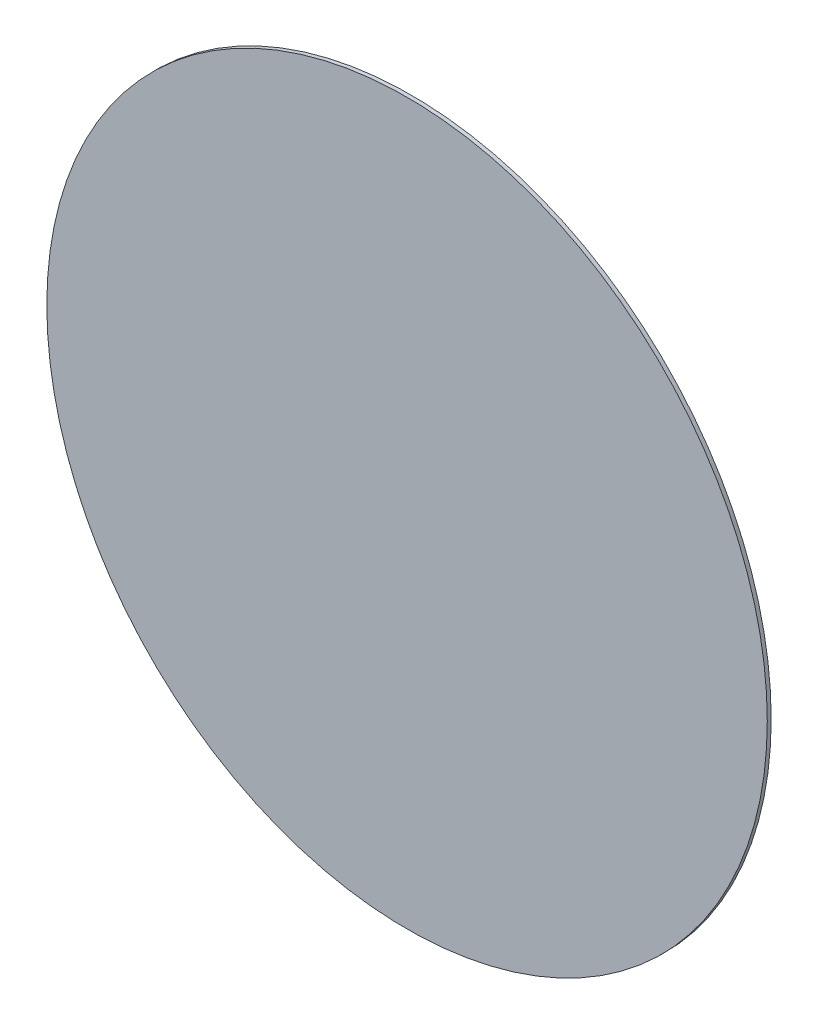
SolidWorks part; units mm, degrees
ref_plane "Front" through (0, 0, 0) normal (0, 0, 1) x (1, 0, 0)
ref_plane "Top" through (0, 0, 0) normal (0, 1, 0) x (1, 0, 0)
ref_plane "Right" through (0, 0, 0) normal (1, 0, 0) x (0, 0, -1)
sketch "Эскиз1" plane through (0, 0, 0) normal (0, 0, 1) x (1, 0, 0)
  circle A0 centre (0, 0) radius 18.5
  dimension "D1" = 37
extrude "Бобышка-Вытянуть1" add sketch "Эскиз1" along normal blind 0.2
